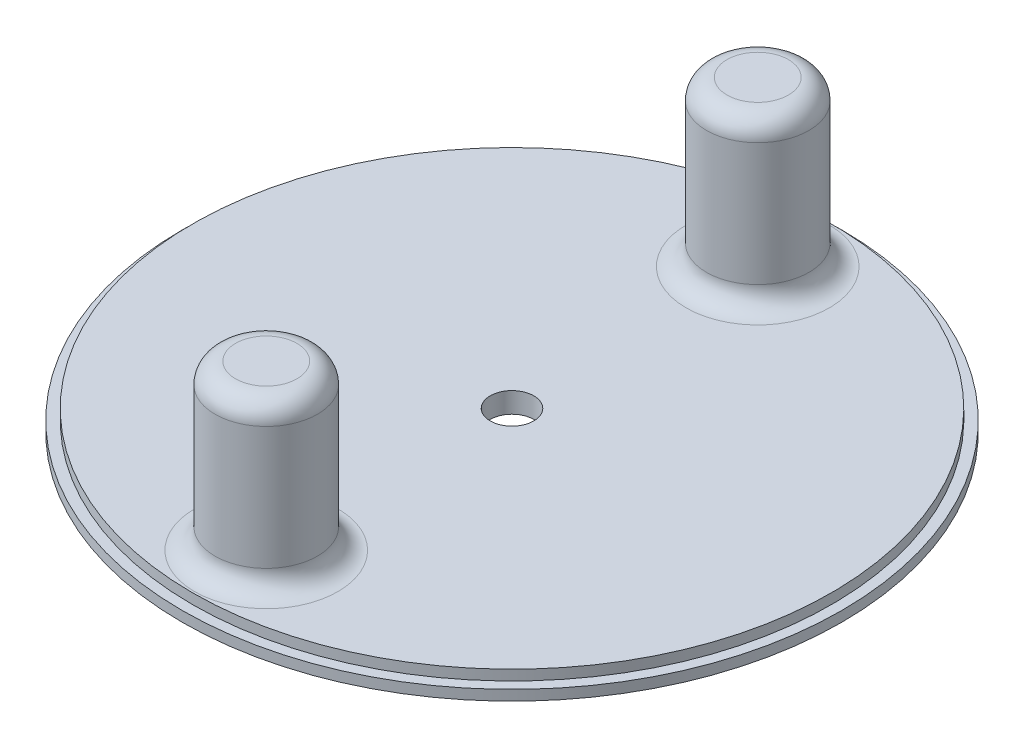
SolidWorks part; units mm, degrees
material "6061-T6 (SS)"
ref_plane "Front Plane" through (0, 0, 0) normal (0, 0, 1) x (1, 0, 0)
ref_plane "Top Plane" through (0, 0, 0) normal (0, 1, 0) x (1, 0, 0)
ref_plane "Right Plane" through (0, 0, 0) normal (1, 0, 0) x (0, 0, -1)
sketch "Sketch1" plane through (0, 0, 0) normal (0, 1, 0) x (1, 0, 0)
  circle A0 centre (0, 0) radius 51.1175
  dimension "D1" = 102.235
extrude "Boss-Extrude1" add sketch "Sketch1" along normal blind 1.5875
sketch "Sketch2" plane through (0, 1.5875, 0) normal (0, 1, 0) x (1, 0, 0)
  circle A0 centre (0, 0) radius 49.53
  dimension "D1" = 99.06
extrude "Boss-Extrude2" add sketch "Sketch2" along normal blind 1.5875
hole_wizard "1/4 Clearance Hole1" positions "Sketch4" profile "Sketch3" hole size "1/4" standard "ANSI Inch"
sketch "Sketch4" plane through (0, 3.175, 0) normal (0, 1, 0) x (1, 0, 0)
  point P0 (0, 0)
sketch "Sketch3" plane through (0, 3.175, 0) normal (1, 0, 0) x (0, 0, 1)
  line L0 (0, 0) -> (0, 27.4298)
  line L1 (0, 27.4298) -> (3.3782, 25.4)
  line L2 (3.3782, 25.4) -> (3.3782, 0)
  line L5 (3.3782, 0) -> (0, 0)
  line L10 (0, 27.4298) -> (-3.3782, 25.4) construction
  line L11 (0, -6.35) -> (0, 107.95) construction
  dimension "Hole Dia." = 6.7564
  dimension "Hole Depth" = 25.4
  dimension "Drill Angle" = 118
sketch "Sketch8" plane through (0, 3.175, 0) normal (0, 1, 0) x (1, 0, 0)
  line L0 (0, 38.1) -> (0, -38.1) construction
  circle A0 centre (0, 38.1) radius 7.9375
  circle A1 centre (0, -38.1) radius 7.9375
  dimension "D1" = 15.875
  dimension "D2" = 76.2
extrude "Boss-Extrude4" add sketch "Sketch8" along normal blind 25.4
sketch "Sketch11" plane through (0, 28.575, 0) normal (0, 1, 0) x (1, 0, 0)
  circle A0 centre (0, -38.1) radius 6.35
  circle A1 centre (0, 38.1) radius 6.35
  dimension "D1" = 12.7
extrude "Cut-Extrude2" cut sketch "Sketch11" against normal through all from offset 1.5875 offset against normal yes
fillet "Fillet1" radius 3.175 6 edges at (0, 26.9875, -31.75) (0, 26.9875, 44.45) (0, 3.175, -30.1625) (0, 3.175, 46.0375) (0, 28.575, -30.1625) (0, 28.575, 46.0375)
